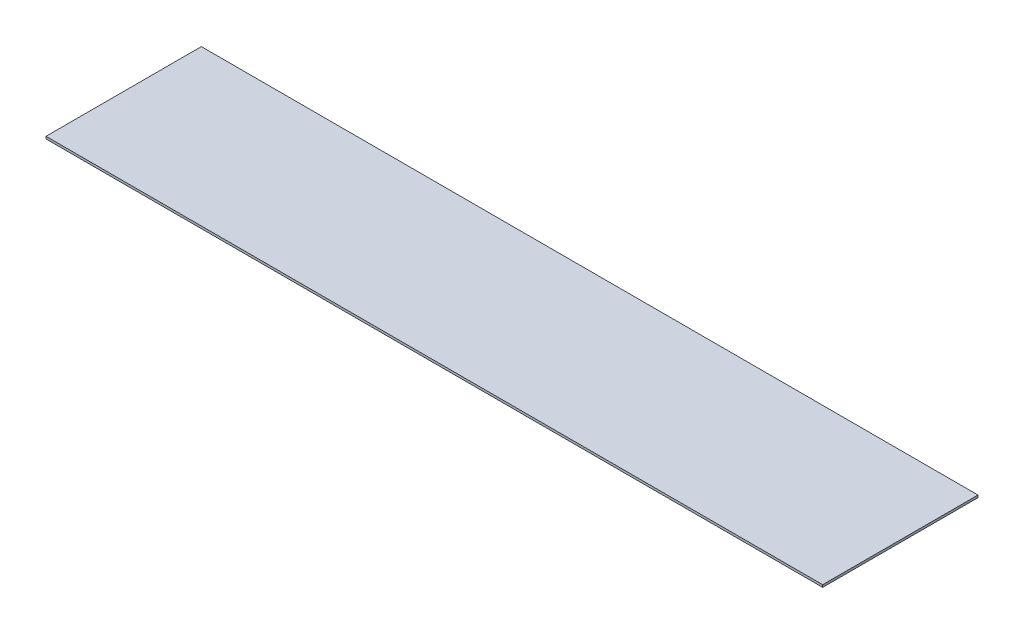
SolidWorks part; units mm, degrees
material "Brass"
ref_plane "Front Plane" through (0, 0, 0) normal (0, 0, 1) x (1, 0, 0)
ref_plane "Top Plane" through (0, 0, 0) normal (0, 1, 0) x (1, 0, 0)
ref_plane "Right Plane" through (0, 0, 0) normal (1, 0, 0) x (0, 0, -1)
other "Configuration Table"
sketch "Sketch1" plane through (0, 0, 0) normal (0, 1, 0) x (1, 0, 0)
  line L1 (-500, 100) -> (500, 100)
  line L2 (-500, 100) -> (-500, -100)
  line L3 (-500, -100) -> (500, -100)
  line L4 (500, 100) -> (500, -100)
  line L5 (-500, 100) -> (500, -100) construction
  line L6 (-500, -100) -> (500, 100) construction
  point P0 (0, 0)
  dimension "D1" = 200
  dimension "D2" = 1000
extrude "Extrude1" add sketch "Sketch1" along normal blind 3
